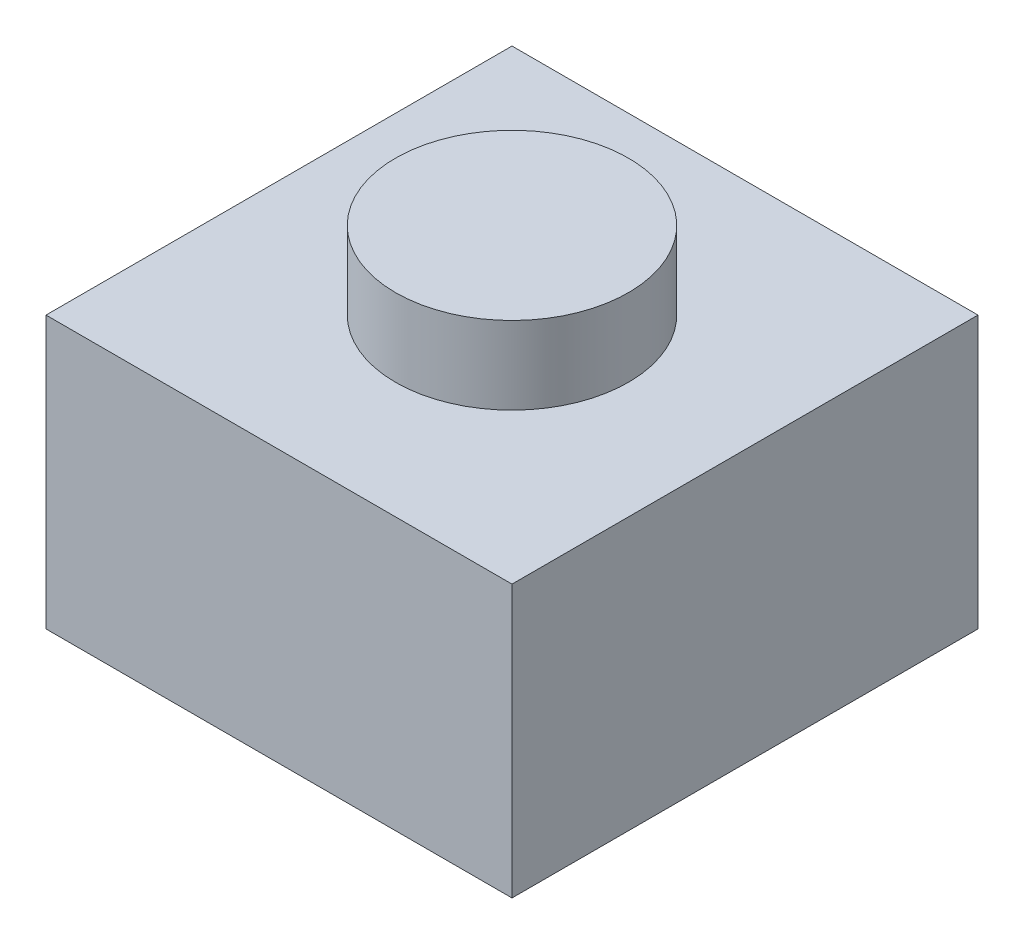
SolidWorks part; units mm, degrees
other "Исправление2"
sketch "Эскиз4" plane through (6, 4.5, 0) normal (0.9437, 0.1201, -0.3083) x (-0.2969, -0.1035, -0.9493)
other "Исправление4"
sketch "Эскиз6"
other "Исправление5"
sketch "Эскиз7"
other "Исправление6"
sketch "Эскиз8"
ref_plane "Спереди" through (0, 0, 0) normal (0, 0, 1) x (1, 0, 0)
ref_plane "Сверху" through (0, 0, 0) normal (0, 1, 0) x (1, 0, 0)
ref_plane "Справа" through (0, 0, 0) normal (1, 0, 0) x (0, 0, -1)
other "Configuration Table"
sketch "Эскиз1" plane through (0, 0, 0) normal (0, 1, 0) x (1, 0, 0)
  line L1 (0, 0) -> (6, 0)
  line L2 (0, 0) -> (0, -6)
  line L3 (0, -6) -> (6, -6)
  line L4 (6, 0) -> (6, -6)
  dimension "D1" = 6
  dimension "D2" = 6
extrude "Бобышка-Вытянуть1" add sketch "Эскиз1" along normal blind 3.5
sketch "Эскиз2" plane through (0, 3.5, 0) normal (0, 1, 0) x (1, 0, 0)
  line L0 (0, 0) -> (0, -6) construction
  line L1 (6, 0) -> (0, 0) construction
  circle A0 centre (3, -3) radius 1.5
  dimension "D1" = 3
  dimension "D3" = 3
  dimension "D2" = 3
extrude "Бобышка-Вытянуть2" add sketch "Эскиз2" along normal blind 1
